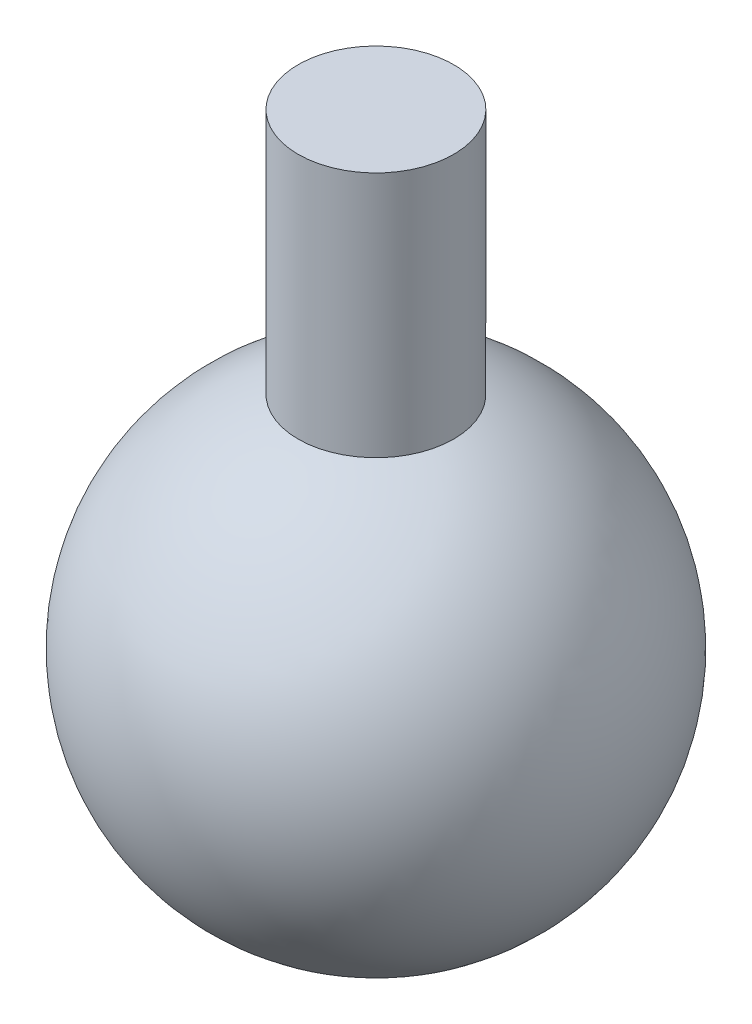
SolidWorks part; units mm, degrees
ref_plane "Front Plane" through (0, 0, 0) normal (0, 0, 1) x (1, 0, 0)
ref_plane "Top Plane" through (0, 0, 0) normal (0, 1, 0) x (1, 0, 0)
ref_plane "Right Plane" through (0, 0, 0) normal (1, 0, 0) x (0, 0, -1)
sketch "Sketch1" plane through (0, 0, 0) normal (0, 0, 1) x (1, 0, 0)
  line L0 (0, 75) -> (0, -75)
  arc A0 (0, -75) -> (0, 75) centre (0, 0) ccw
  dimension "D1" = 150
revolve "Revolve1" add sketch "Sketch1" angle 360 about L0
ref_plane "Plane1" through (0, 75, 0) normal (0, 1, 0) x (1, 0, 0)
sketch "Sketch2" plane through (0, 75, 0) normal (0, 1, 0) x (1, 0, 0)
  circle A0 centre (0, 0) radius 25
  dimension "D1" = 50
extrude "Boss-Extrude1" add sketch "Sketch2" along normal blind 75 and the other way blind 10
